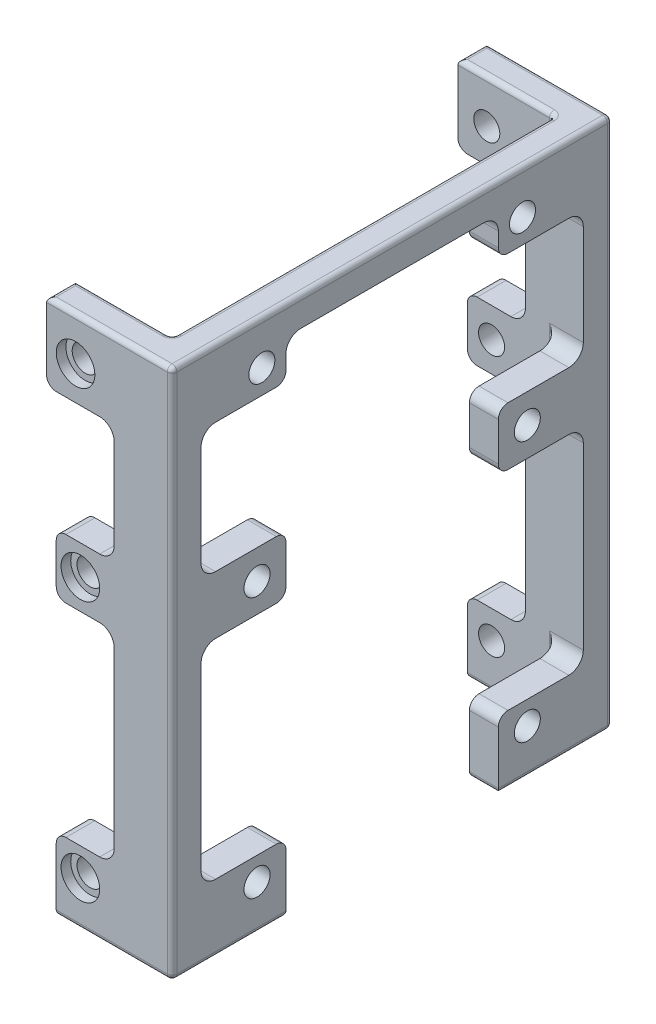
SolidWorks part; units mm, degrees
material "Esun Hard Tough Resin"
ref_plane "Front Plane" through (0, 0, 0) normal (0, 0, 1) x (1, 0, 0)
ref_plane "Top Plane" through (0, 0, 0) normal (0, 1, 0) x (1, 0, 0)
ref_plane "Right Plane" through (0, 0, 0) normal (1, 0, 0) x (0, 0, -1)
sketch "Sketch2" plane through (0, 0, 0) normal (0, 0, 1) x (1, 0, 0)
  line L0 (-6, -15.9661) -> (-6, 28)
  line L1 (6, -28) -> (-6, -28)
  line L2 (6, -28) -> (6, 28)
  line L3 (6, 28) -> (-6, 28)
  line L4 (-6, -28) -> (-6, -15.9661)
  line L5 (6, -28) -> (-6, 28) construction
  line L6 (6, 28) -> (-6, -28) construction
  point P0 (0, 0)
  dimension "D1" = 56
  dimension "D2" = 12
extrude "Boss-Extrude1" add sketch "Sketch2" along normal blind 3
sketch "Sketch3" plane through (0, 0, 0) normal (0, 0, -1) x (-1, 0, 0)
  line L0 (6, -28) -> (-6, -28) construction
  line L1 (-6, 28) -> (-3, 28)
  line L2 (-6, 28) -> (-6, -28)
  line L3 (-6, -28) -> (-3, -28)
  line L4 (-3, 28) -> (-3, -28)
  dimension "D1" = 3
extrude "Boss-Extrude2" add sketch "Sketch3" along normal blind 8.8
sketch "Sketch4" plane through (3, 0, 0) normal (-1, 0, 0) x (0, 0, 1)
  line L0 (-8.8, -28) -> (-8.8, 28) construction
  line L1 (-8.8, 1.6) -> (0, 1.6)
  line L2 (-8.8, 1.6) -> (-8.8, -20)
  line L3 (-8.8, -20) -> (0, -20)
  line L4 (0, 1.6) -> (0, -20)
  line L6 (-8.8, -28) -> (0, -28) construction
  line L7 (0, 28) -> (0, -28) construction
  line L8 (-8.8, 28) -> (0, 28) construction
  line L9 (-8.8, 21) -> (0, 21)
  line L10 (-8.8, 21) -> (-8.8, 7.6)
  line L11 (-8.8, 7.6) -> (0, 7.6)
  line L12 (0, 21) -> (0, 7.6)
  dimension "D1" = 21.6
  dimension "D2" = 8
  dimension "D3" = 13.4
  dimension "D4" = 7
extrude "Cut-Extrude1" cut sketch "Sketch4" against normal through all
sketch "Sketch5" plane through (0, 0, 3) normal (0, 0, 1) x (1, 0, 0)
  line L0 (-6, 28) -> (-6, -28) construction
  line L1 (-6, 1.52) -> (0, 1.52)
  line L2 (-6, 1.52) -> (-6, -19.5)
  line L3 (-6, -19.5) -> (0, -19.5)
  line L4 (0, 1.52) -> (0, -19.5)
  line L5 (6, 28) -> (-6, 28) construction
  line L6 (-6, 20) -> (0, 20)
  line L7 (-6, 20) -> (-6, 7.68)
  line L8 (-6, 7.68) -> (0, 7.68)
  line L9 (0, 20) -> (0, 7.68)
  line L10 (-6, -28) -> (6, -28) construction
  dimension "D1" = 6
  dimension "D2" = 21.02
  dimension "D3" = 12.32
  dimension "D4" = 8
  dimension "D5" = 8.5
extrude "Cut-Extrude2" cut sketch "Sketch5" against normal through all
sketch "Sketch6" plane through (0, 0, 3) normal (0, 0, 1) x (1, 0, 0)
  line L0 (-6, -28) -> (6, -28) construction
  line L1 (0, -19.5) -> (0, 1.52) construction
  line L2 (0, 7.68) -> (0, 20) construction
  circle A0 centre (-4, 23.5) radius 1.35
  circle A1 centre (-3.5, 4.6) radius 1.35
  circle A2 centre (-3.5, -22.4) radius 1.35
  dimension "D1" = 2.7
  dimension "D2" = 18.9
  dimension "D3" = 27
  dimension "D4" = 5.6
  dimension "D5" = 3.5
  dimension "D6" = 3.5
  dimension "D7" = 4
extrude "Cut-Extrude3" cut sketch "Sketch6" against normal through all
sketch "Sketch8" plane through (6, 0, 0) normal (1, 0, 0) x (0, 0, -1)
  line L0 (8.8, 28) -> (8.8, 21) construction
  line L1 (8.8, -20) -> (8.8, -28) construction
  line L2 (-3, -28) -> (8.8, -28) construction
  line L13 (8.8, 7.6) -> (8.8, 1.6) construction
  circle A0 centre (6.3, 23.5) radius 1.35
  circle A1 centre (5.8, 4.6) radius 1.35
  circle A2 centre (5.8, -22.4) radius 1.35
  dimension "D1" = 2.7
  dimension "D2" = 18.9
  dimension "D3" = 27
  dimension "D4" = 2.5
  dimension "D5" = 3
  dimension "D6" = 5.6
  dimension "D9" = 3
extrude "Cut-Extrude5" cut sketch "Sketch8" against normal through all
sketch "Sketch10" plane through (0, 0, -8.8) normal (0, 0, -1) x (-1, 0, 0)
  line L0 (-3, 21) -> (-3, 28) construction
  line L6 (-6, 28) -> (-3, 28)
  line L8 (-6, 28) -> (-6, 25)
  line L9 (-6, 25) -> (-3, 25)
  line L10 (-3, 28) -> (-3, 25)
  dimension "D1" = 3
extrude "Boss-Extrude3" add sketch "Sketch10" along normal blind 11
mirror "Mirror3" about plane through (0, 0, -19.8) normal (0, 0, -1) of bodies 108
sketch "Sketch11" plane through (-6, 0, 0) normal (-1, 0, 0) x (0, 0, 1)
  line L0 (0, 28) -> (0, 20) construction
  line L1 (0, 20) -> (3, 20) construction
  line L2 (3, 20) -> (3, 28) construction
  line L3 (3, 28) -> (0, 28) construction
  line L4 (-39.6, 20) -> (-39.6, 28) construction
  line L5 (-39.6, 28) -> (-42.6, 28) construction
  line L6 (-42.6, 28) -> (-42.6, 20) construction
  line L7 (-42.6, 20) -> (-39.6, 20) construction
  line L8 (0, 28) -> (0, 20)
  line L9 (0, 20) -> (3, 20)
  line L10 (3, 20) -> (3, 28)
  line L11 (3, 28) -> (0, 28)
  line L12 (-39.6, 20) -> (-39.6, 28)
  line L13 (-39.6, 28) -> (-42.6, 28)
  line L14 (-42.6, 28) -> (-42.6, 20)
  line L15 (-42.6, 20) -> (-39.6, 20)
extrude "Boss-Extrude4" add sketch "Sketch11" along normal blind 1
sketch "Sketch12" plane through (0, -28, 0) normal (0, -1, 0) x (1, 0, 0)
  line L1 (6, -42.6) -> (-6, -42.6)
  line L2 (6, -42.6) -> (6, 3)
  line L3 (6, 3) -> (-6, 3)
  line L4 (-6, -42.6) -> (-6, 3)
extrude "Cut-Extrude6" cut sketch "Sketch12" against normal blind 1
fillet "Fillet1" radius 1 16 edges at (-6, 7.68, -41.1) (4.5, 7.6, -30.8) (-6, -19.5, -41.1) (4.5, -20, -30.8) (4.5, 21, -30.8) (4.5, 1.6, -30.8) (-6, 1.52, -41.1) (-7, 20, 1.5) (-7, 20, -41.1) (4.5, -20, -8.8) (4.5, 1.6, -8.8) (4.5, 7.6, -8.8) (4.5, 21, -8.8) (-6, -19.5, 1.5) (-6, 1.52, 1.5) (-6, 7.68, 1.5)
fillet "Fillet2" radius 1.5 18 edges at (4.5, 25, -8.8) (4.5, 25, -30.8) (4.5, 1.6, -39.6) (4.5, 21, -39.6) (4.5, 7.6, -39.6) (4.5, -20, -39.6) (0, 20, -41.1) (0, 7.68, -41.1) (0, 1.52, -41.1) (0, -19.5, -41.1) (4.5, 1.6, 0) (4.5, -20, 0) (4.5, 21, 0) (4.5, 7.6, 0) (0, 1.52, 1.5) (0, -19.5, 1.5) (0, 20, 1.5) (0, 7.68, 1.5)
fillet "Fillet3" radius 0.5 28 edges at (-0.5, 28, -42.6) (3, 4.6, -39.6) (3, 23.75, -39.6) (-2, 28, -39.6) (-2, 28, 0) (3, 28, -19.8) (-7, 28, 1.5) (-7, 28, -41.1) (4.5, -27, -30.8) (3, -22.75, -39.6) (6, 0.5, -42.6) (3, -22.75, 0) (6, 0.5, 3) (-6, -27, 1.5) (6, -27, -2.9) (3, -27, -4.4) (3, -27, -35.2) (-1.5, -27, 0) (4.5, -27, -8.8) (6, -27, -36.7) (0, -27, -42.6) (-6, -27, -41.1) (0, -27, 3) (-1.5, -27, -39.6) (3, 4.6, 0) (3, 23.75, 0) (-0.5, 28, 3) (6, 28, -19.8)
sketch "Sketch13" plane through (3, 0, 0) normal (-1, 0, 0) x (0, 0, 1)
  line L0 (-29.3, 25) -> (-10.3, 25) construction
  line L1 (-29.3, 25) -> (-10.3, 25) construction
  line L2 (-19.8, -993.2431) -> (-19.8, 49006.7569) construction
  circle A0 centre (-33.3, 23.5) radius 2
  circle A1 centre (-33.8, 4.6) radius 2
  circle A2 centre (-33.8, -22.4) radius 2
  circle A3 centre (-5.8, -22.4) radius 2
  circle A4 centre (-5.8, 4.6) radius 2
  circle A5 centre (-6.3, 23.5) radius 2
  point P12 (-19.8, 25)
  dimension "D1" = 4
extrude "Cut-Extrude7" cut sketch "Sketch13" against normal blind 1
sketch "Sketch14" plane through (0, 0, -42.6) normal (0, 0, -1) x (-1, 0, 0)
  circle A0 centre (4, 23.5) radius 2
  circle A1 centre (3.5, 4.6) radius 2
  circle A2 centre (3.5, -22.4) radius 2
  dimension "D1" = 4
extrude "Cut-Extrude8" cut sketch "Sketch14" against normal blind 1
ref_plane "Plane1" through (0, 0, -19.8) normal (0, 0, -1) x (-1, 0, 0)
mirror "Mirror4" about plane through (0, 0, -19.8) normal (0, 0, -1) of "Cut-Extrude8"
